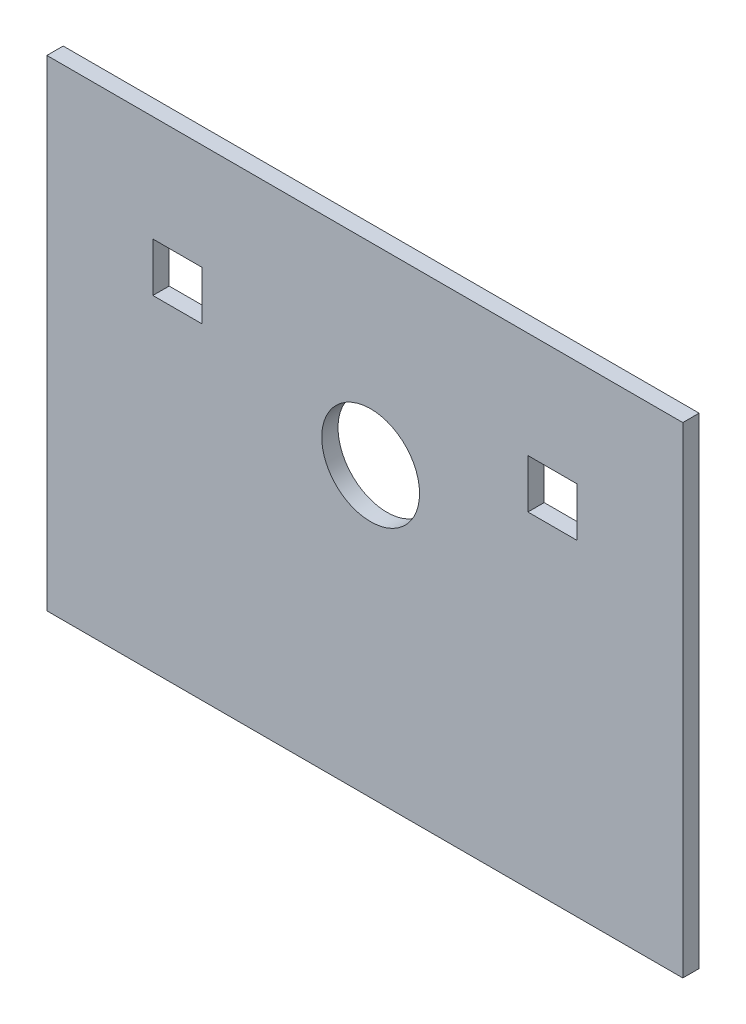
SolidWorks part; units mm, degrees
ref_plane "Front Plane" through (0, 0, 0) normal (0, 0, 1) x (1, 0, 0)
ref_plane "Top Plane" through (0, 0, 0) normal (0, 1, 0) x (1, 0, 0)
ref_plane "Right Plane" through (0, 0, 0) normal (1, 0, 0) x (0, 0, -1)
sketch "Sketch1" plane through (0, 0, 0) normal (0, 0, 1) x (1, 0, 0)
  line L0 (-23, 13.5) -> (23, 13.5) construction
  line L1 (-39, -29.5) -> (39, -29.5)
  line L2 (-39, -29.5) -> (-39, 29.5)
  line L3 (-39, 29.5) -> (39, 29.5)
  line L4 (39, -29.5) -> (39, 29.5)
  line L5 (-39, -29.5) -> (39, 29.5) construction
  line L6 (-39, 29.5) -> (39, -29.5) construction
  line L7 (-26, 10.5) -> (-20, 10.5)
  line L8 (-26, 10.5) -> (-26, 16.5)
  line L9 (-26, 16.5) -> (-20, 16.5)
  line L10 (-20, 10.5) -> (-20, 16.5)
  line L11 (-26, 10.5) -> (-20, 16.5) construction
  line L12 (-26, 16.5) -> (-20, 10.5) construction
  line L13 (20, 10.5) -> (26, 10.5)
  line L14 (20, 10.5) -> (20, 16.5)
  line L15 (20, 16.5) -> (26, 16.5)
  line L16 (26, 10.5) -> (26, 16.5)
  line L17 (20, 10.5) -> (26, 16.5) construction
  line L18 (20, 16.5) -> (26, 10.5) construction
  line L19 (0, 0) -> (0, 13.5) construction
  circle A0 centre (0.71, 5.82) radius 6.0004
  point P0 (0, 0)
  point P6 (-23, 13.5)
  point P11 (23, 13.5)
  point P16 (0.71, 5.82)
  dimension "D6" = 13
  dimension "D7" = 13
  dimension "D1" = 40
  dimension "D2" = 6
  dimension "D3" = 13.5
  dimension "D4" = 0.71
  dimension "D5" = 7.68
  dimension "D8" = 40
extrude "Boss-Extrude1" add sketch "Sketch1" against normal blind 2
sketch "Sketch3" plane through (0, 0, 0) normal (0, 0, 1) x (1, 0, 0)
  line L1 (-7.6993, 13.1993) -> (9.1193, 13.1993)
  line L2 (-7.6993, 13.1993) -> (-7.6993, 18.9693)
  line L3 (-7.6993, 18.9693) -> (9.1193, 18.9693)
  line L4 (9.1193, 13.1993) -> (9.1193, 18.9693)
  line L5 (-7.6993, 13.1993) -> (9.1193, 18.9693) construction
  line L6 (-7.6993, 18.9693) -> (9.1193, 13.1993) construction
  line L7 (-8.4008, -14.4681) -> (9.8208, -14.4681)
  line L8 (-8.4008, -14.4681) -> (-8.4008, -7.6901)
  line L9 (-8.4008, -7.6901) -> (9.8208, -7.6901)
  line L10 (9.8208, -14.4681) -> (9.8208, -7.6901)
  line L11 (-8.4008, -14.4681) -> (9.8208, -7.6901) construction
  line L12 (-8.4008, -7.6901) -> (9.8208, -14.4681) construction
  circle A0 centre (0.71, 5.82) radius 6.0004 construction
  circle A1 centre (0.71, 5.82) radius 6.0004 construction
  circle A2 centre (5.9626, 16.0843) radius 1.2005
  circle A3 centre (7.3071, -11.0791) radius 1.2005
  circle A4 centre (-5.8457, -11.0791) radius 1.2005
  circle A5 centre (-4.6452, 16.0843) radius 1.2005
  point P3 (0.71, 16.0843)
  point P8 (0.71, -11.0791)
  point P21 (0, 0)
  point P22 (0, 0)
